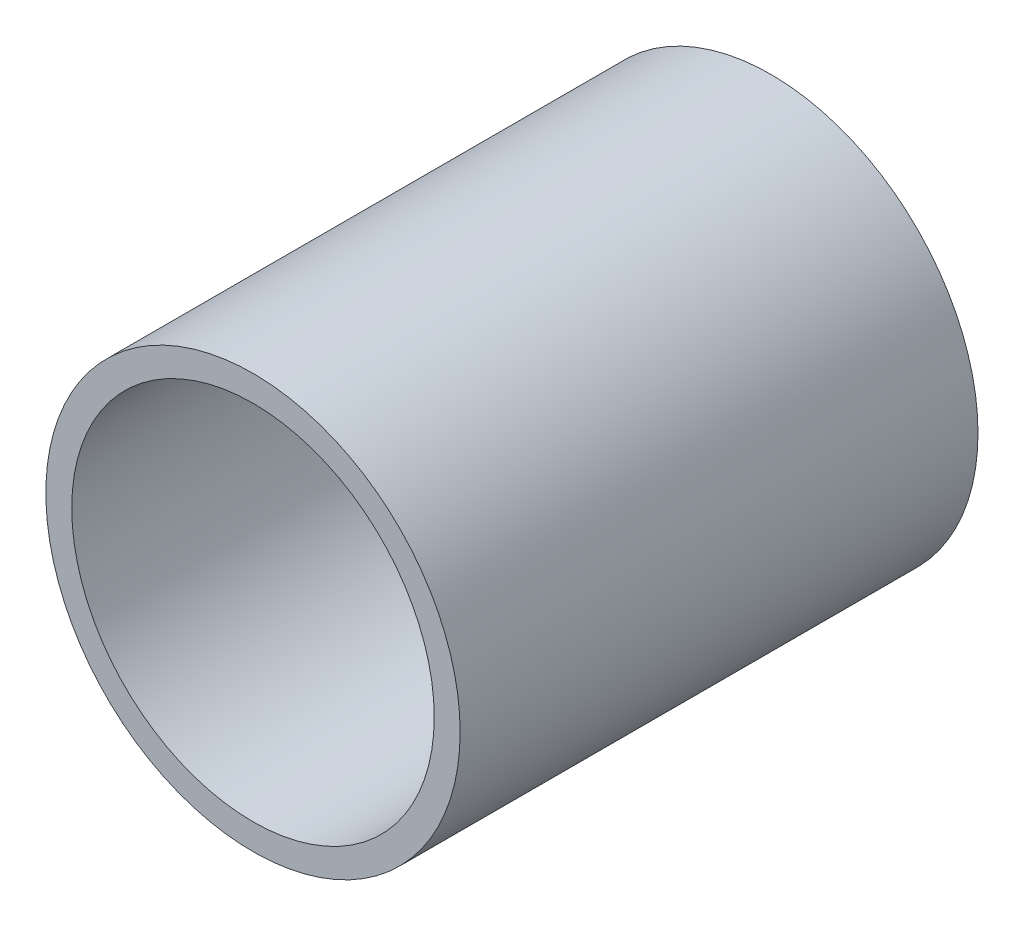
SolidWorks part; units mm, degrees
material "Latón"
ref_plane "Front" through (0, 0, 0) normal (0, 0, 1) x (1, 0, 0)
ref_plane "Top" through (0, 0, 0) normal (0, 1, 0) x (1, 0, 0)
ref_plane "Right" through (0, 0, 0) normal (1, 0, 0) x (0, 0, -1)
sketch "Croquis1" plane through (0, 0, 0) normal (0, 0, 1) x (1, 0, 0)
  circle A0 centre (0, 0) radius 3.5
  circle A1 centre (0, 0) radius 4
  dimension "D1" = 7
  dimension "9" = 8
extrude "Saliente-Extruir1" add sketch "Croquis1" along normal blind 10
